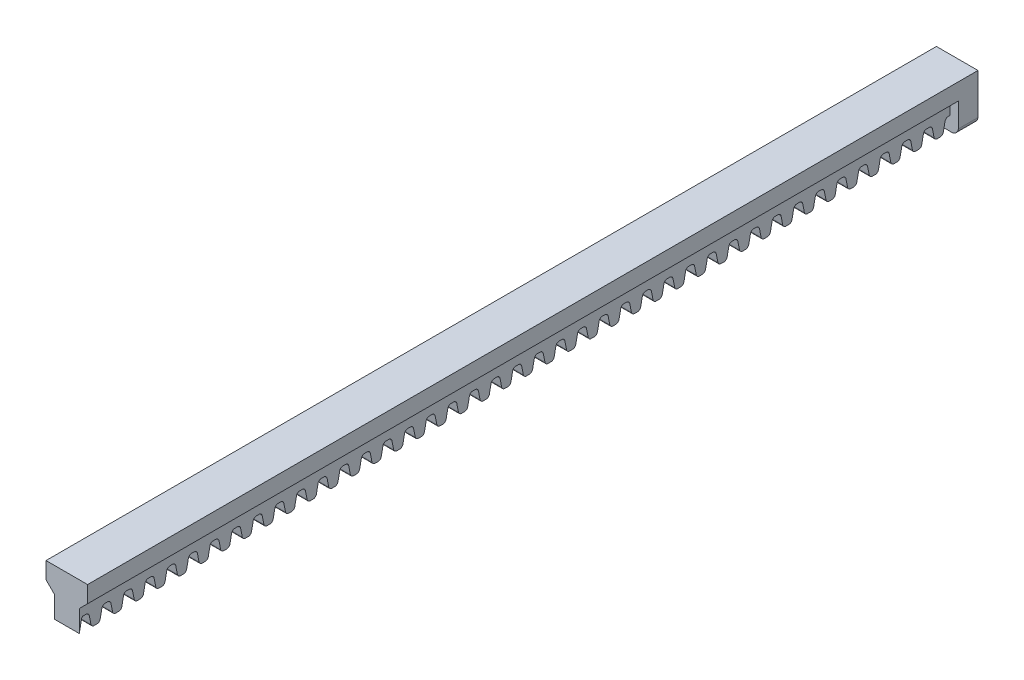
SolidWorks part; units mm, degrees
ref_plane "Ön Düzlem" through (0, 0, 0) normal (0, 0, 1) x (1, 0, 0)
ref_plane "Üst Düzlem" through (0, 0, 0) normal (0, 1, 0) x (1, 0, 0)
ref_plane "Sağ Düzlem" through (0, 0, 0) normal (1, 0, 0) x (0, 0, -1)
sketch "Sketch1" plane through (0, 0, 0) normal (0, 0, 1) x (1, 0, 0)
  line L0 (3.175, 2.54) -> (-3.175, 2.54)
  line L1 (3.175, 2.54) -> (3.175, 0)
  line L2 (-3.175, 0) -> (-1.905, -1.27)
  line L3 (-3.175, 0) -> (-3.175, 2.54)
  line L4 (1.905, -1.27) -> (3.175, 0)
  line L5 (1.905, -1.27) -> (1.905, -2.54)
  line L6 (-1.905, -1.27) -> (-1.905, -2.54)
  line L7 (-1.905, -2.54) -> (1.905, -2.54)
extrude "Boss-Extrude1" add sketch "Sketch1" along normal blind 133
sketch "Sketch2" plane through (1.905, 0, 0) normal (1, 0, 0) x (0, 0, -1)
  line L0 (-4.0649, -2.9484) -> (-4.3253, -4.2507)
  line L1 (-4.7367, -4.6515) -> (-5.2405, -4.659)
  line L2 (-5.7387, -4.2506) -> (-5.9991, -2.9484)
  line L3 (-6.4973, -2.54) -> (-3.5667, -2.54)
  line L4 (-109.7289, -2.9484) -> (-109.9893, -4.2506)
  line L5 (-6.8687, -2.54) -> (-9.7993, -2.54)
  line L6 (-7.6273, -4.2506) -> (-7.3669, -2.9484)
  line L7 (-8.6293, -4.6515) -> (-8.1255, -4.659)
  line L8 (-9.3011, -2.9484) -> (-9.0407, -4.2506)
  line L9 (-10.6689, -2.9484) -> (-10.9293, -4.2506)
  line L10 (-11.3407, -4.6515) -> (-11.8445, -4.659)
  line L11 (-12.3427, -4.2506) -> (-12.6031, -2.9484)
  line L12 (-13.1013, -2.54) -> (-10.1707, -2.54)
  line L13 (-13.4727, -2.54) -> (-16.4033, -2.54)
  line L14 (-14.2313, -4.2506) -> (-13.9709, -2.9484)
  line L15 (-15.2333, -4.6515) -> (-14.7295, -4.659)
  line L16 (-15.9051, -2.9484) -> (-15.6447, -4.2506)
  line L17 (-17.2729, -2.9484) -> (-17.5334, -4.2506)
  line L18 (-17.9447, -4.6515) -> (-18.4486, -4.659)
  line L19 (-18.9467, -4.2506) -> (-19.2072, -2.9484)
  line L20 (-19.7053, -2.54) -> (-16.7748, -2.54)
  line L21 (-20.0768, -2.54) -> (-23.0073, -2.54)
  line L22 (-20.8353, -4.2506) -> (-20.5749, -2.9484)
  line L23 (-21.8373, -4.6515) -> (-21.3335, -4.659)
  line L24 (-22.5092, -2.9484) -> (-22.2487, -4.2506)
  line L25 (-23.8769, -2.9484) -> (-24.1373, -4.2506)
  line L26 (-24.5487, -4.6515) -> (-25.0526, -4.659)
  line L27 (-25.5507, -4.2506) -> (-25.8111, -2.9484)
  line L28 (-26.3093, -2.54) -> (-23.3788, -2.54)
  line L29 (-26.6807, -2.54) -> (-29.6113, -2.54)
  line L30 (-27.4393, -4.2506) -> (-27.1789, -2.9484)
  line L31 (-28.4413, -4.6515) -> (-27.9375, -4.659)
  line L32 (-29.1131, -2.9484) -> (-28.8527, -4.2506)
  line L33 (-30.4809, -2.9484) -> (-30.7413, -4.2506)
  line L34 (-31.1527, -4.6515) -> (-31.6565, -4.659)
  line L35 (-32.1547, -4.2506) -> (-32.4151, -2.9484)
  line L36 (-32.9133, -2.54) -> (-29.9827, -2.54)
  line L37 (-33.2847, -2.54) -> (-36.2153, -2.54)
  line L38 (-34.0433, -4.2506) -> (-33.7829, -2.9484)
  line L39 (-35.0453, -4.6515) -> (-34.5415, -4.659)
  line L40 (-35.7171, -2.9484) -> (-35.4567, -4.2506)
  line L41 (-37.0849, -2.9484) -> (-37.3453, -4.2506)
  line L42 (-37.7567, -4.6515) -> (-38.2605, -4.659)
  line L43 (-38.7587, -4.2506) -> (-39.0191, -2.9484)
  line L44 (-39.5173, -2.54) -> (-36.5867, -2.54)
  line L45 (-39.8887, -2.54) -> (-42.8193, -2.54)
  line L46 (-40.6473, -4.2506) -> (-40.3869, -2.9484)
  line L47 (-41.6493, -4.6515) -> (-41.1455, -4.659)
  line L48 (-42.3211, -2.9484) -> (-42.0607, -4.2506)
  line L49 (-43.6889, -2.9484) -> (-43.9494, -4.2506)
  line L50 (-44.3607, -4.6515) -> (-44.8646, -4.659)
  line L51 (-45.3627, -4.2506) -> (-45.6231, -2.9484)
  line L52 (-46.1213, -2.54) -> (-43.1908, -2.54)
  line L53 (-46.4928, -2.54) -> (-49.4233, -2.54)
  line L54 (-47.2513, -4.2506) -> (-46.9909, -2.9484)
  line L55 (-48.2533, -4.6515) -> (-47.7495, -4.659)
  line L56 (-48.9251, -2.9484) -> (-48.6647, -4.2506)
  line L57 (-50.2929, -2.9484) -> (-50.5533, -4.2506)
  line L58 (-50.9647, -4.6515) -> (-51.4685, -4.659)
  line L59 (-51.9667, -4.2506) -> (-52.2271, -2.9484)
  line L60 (-52.7253, -2.54) -> (-49.7947, -2.54)
  line L61 (-53.0967, -2.54) -> (-56.0273, -2.54)
  line L62 (-53.8553, -4.2506) -> (-53.5949, -2.9484)
  line L63 (-54.8573, -4.6515) -> (-54.3535, -4.659)
  line L64 (-55.5291, -2.9484) -> (-55.2687, -4.2506)
  line L65 (-56.8969, -2.9484) -> (-57.1573, -4.2506)
  line L66 (-57.5687, -4.6515) -> (-58.0725, -4.659)
  line L67 (-58.5707, -4.2506) -> (-58.8311, -2.9484)
  line L68 (-59.3293, -2.54) -> (-56.3987, -2.54)
  line L69 (-59.7007, -2.54) -> (-62.6313, -2.54)
  line L70 (-60.4593, -4.2506) -> (-60.1989, -2.9484)
  line L71 (-61.4613, -4.6515) -> (-60.9575, -4.659)
  line L72 (-62.1331, -2.9484) -> (-61.8727, -4.2506)
  line L73 (-63.5009, -2.9484) -> (-63.7613, -4.2506)
  line L74 (-64.1727, -4.6515) -> (-64.6765, -4.659)
  line L75 (-65.1747, -4.2506) -> (-65.4351, -2.9484)
  line L76 (-65.9332, -2.54) -> (-63.0027, -2.54)
  line L77 (-66.3047, -2.54) -> (-69.2353, -2.54)
  line L78 (-67.0633, -4.2506) -> (-66.8029, -2.9484)
  line L79 (-68.0653, -4.6515) -> (-67.5614, -4.659)
  line L80 (-68.7371, -2.9484) -> (-68.4767, -4.2506)
  line L81 (-70.1049, -2.9484) -> (-70.3653, -4.2506)
  line L82 (-70.7767, -4.6515) -> (-71.2806, -4.659)
  line L83 (-71.7787, -4.2506) -> (-72.0391, -2.9484)
  line L84 (-72.5373, -2.54) -> (-69.6068, -2.54)
  line L85 (-72.9088, -2.54) -> (-75.8393, -2.54)
  line L86 (-73.6673, -4.2506) -> (-73.4069, -2.9484)
  line L87 (-74.6693, -4.6515) -> (-74.1655, -4.659)
  line L88 (-75.3411, -2.9484) -> (-75.0807, -4.2506)
  line L89 (-76.7089, -2.9484) -> (-76.9693, -4.2506)
  line L90 (-77.3807, -4.6515) -> (-77.8845, -4.659)
  line L91 (-78.3827, -4.2506) -> (-78.6431, -2.9484)
  line L92 (-79.1413, -2.54) -> (-76.2107, -2.54)
  line L93 (-79.5127, -2.54) -> (-82.4433, -2.54)
  line L94 (-80.2713, -4.2506) -> (-80.0109, -2.9484)
  line L95 (-81.2733, -4.6515) -> (-80.7695, -4.659)
  line L96 (-81.9451, -2.9484) -> (-81.6847, -4.2506)
  line L97 (-83.3129, -2.9484) -> (-83.5733, -4.2506)
  line L98 (-83.9847, -4.6515) -> (-84.4885, -4.659)
  line L99 (-84.9867, -4.2506) -> (-85.2471, -2.9484)
  line L100 (-85.7453, -2.54) -> (-82.8147, -2.54)
  line L101 (-86.1167, -2.54) -> (-89.0473, -2.54)
  line L102 (-86.8753, -4.2506) -> (-86.6149, -2.9484)
  line L103 (-87.8773, -4.6515) -> (-87.3735, -4.659)
  line L104 (-88.5491, -2.9484) -> (-88.2887, -4.2506)
  line L105 (-89.9169, -2.9484) -> (-90.1773, -4.2506)
  line L106 (-90.5887, -4.6515) -> (-91.0925, -4.659)
  line L107 (-91.5907, -4.2506) -> (-91.8511, -2.9484)
  line L108 (-92.3492, -2.54) -> (-89.4187, -2.54)
  line L109 (-92.7207, -2.54) -> (-95.6513, -2.54)
  line L110 (-93.4793, -4.2506) -> (-93.2189, -2.9484)
  line L111 (-94.4813, -4.6515) -> (-93.9774, -4.659)
  line L112 (-95.1531, -2.9484) -> (-94.8927, -4.2506)
  line L113 (-96.5209, -2.9484) -> (-96.7813, -4.2506)
  line L114 (-97.1927, -4.6515) -> (-97.6966, -4.659)
  line L115 (-98.1947, -4.2506) -> (-98.4551, -2.9484)
  line L116 (-98.9533, -2.54) -> (-96.0228, -2.54)
  line L117 (-99.3247, -2.54) -> (-102.2553, -2.54)
  line L118 (-100.0833, -4.2506) -> (-99.8229, -2.9484)
  line L119 (-101.0853, -4.6515) -> (-100.5815, -4.659)
  line L120 (-101.7571, -2.9484) -> (-101.4967, -4.2506)
  line L121 (-103.1249, -2.9484) -> (-103.3853, -4.2506)
  line L122 (-103.7967, -4.6515) -> (-104.3005, -4.659)
  line L123 (-104.7987, -4.2506) -> (-105.0591, -2.9484)
  line L124 (-105.5573, -2.54) -> (-102.6267, -2.54)
  line L125 (-105.9287, -2.54) -> (-108.8593, -2.54)
  line L126 (-106.6873, -4.2506) -> (-106.4269, -2.9484)
  line L127 (-107.6893, -4.6515) -> (-107.1855, -4.659)
  line L128 (-108.3611, -2.9484) -> (-108.1007, -4.2506)
  line L129 (-110.4007, -4.6515) -> (-110.9045, -4.659)
  line L130 (-111.4027, -4.2506) -> (-111.6631, -2.9484)
  line L131 (-112.1613, -2.54) -> (-109.2307, -2.54)
  line L132 (-112.5327, -2.54) -> (-115.4633, -2.54)
  line L133 (-113.2913, -4.2506) -> (-113.0309, -2.9484)
  line L134 (-114.2933, -4.6515) -> (-113.7895, -4.659)
  line L135 (-114.9651, -2.9484) -> (-114.7047, -4.2506)
  line L136 (-116.3329, -2.9484) -> (-116.5933, -4.2506)
  line L137 (-117.0047, -4.6515) -> (-117.5085, -4.659)
  line L138 (-118.0067, -4.2506) -> (-118.2671, -2.9484)
  line L139 (-118.7652, -2.54) -> (-115.8347, -2.54)
  line L140 (-119.1367, -2.54) -> (-122.0673, -2.54)
  line L141 (-119.8953, -4.2506) -> (-119.6349, -2.9484)
  line L142 (-120.8973, -4.6515) -> (-120.3934, -4.659)
  line L143 (-121.5691, -2.9484) -> (-121.3087, -4.2506)
  line L144 (-122.9369, -2.9484) -> (-123.1973, -4.2506)
  line L145 (-123.6087, -4.6515) -> (-124.1126, -4.659)
  line L146 (-124.6107, -4.2506) -> (-124.8711, -2.9484)
  line L147 (-125.3693, -2.54) -> (-122.4388, -2.54)
  line L148 (-125.7408, -2.54) -> (-128.6713, -2.54)
  line L149 (-126.4993, -4.2506) -> (-126.2389, -2.9484)
  line L150 (-127.5013, -4.6515) -> (-126.9975, -4.659)
  line L151 (-128.1731, -2.9484) -> (-127.9127, -4.2506)
  line L152 (-129.5409, -2.9484) -> (-129.8013, -4.2506)
  line L153 (-130.2127, -4.6515) -> (-130.7165, -4.659)
  line L154 (-131.2147, -4.2506) -> (-131.4751, -2.9484)
  line L155 (-131.9733, -2.54) -> (-129.0427, -2.54)
  line L156 (-133, -2.54) -> (-133, -4.5784)
  line L157 (-133, -4.5784) -> (-132.6341, -2.749)
  line L158 (-133, -2.54) -> (-132.3792, -2.54)
  line L160 (-133, -2.54) -> (0, -2.54) construction
  line L161 (-133, -2.54) -> (-133, -1.27) construction
  line L163 (-0.2651, -2.54) -> (-3.1956, -2.54)
  line L164 (-1.0237, -4.2506) -> (-0.7632, -2.9484)
  line L165 (-2.0257, -4.6515) -> (-1.5218, -4.659)
  line L166 (-2.6975, -2.9484) -> (-2.437, -4.2507)
  arc A0 (-4.0649, -2.9484) -> (-3.5667, -2.54) centre (-3.5667, -3.048) cw
  arc A1 (-4.3253, -4.2507) -> (-4.7367, -4.6515) centre (-4.8234, -4.151) cw
  arc A2 (-5.2405, -4.659) -> (-5.7387, -4.2506) centre (-5.2405, -4.151) cw
  arc A3 (-5.9991, -2.9484) -> (-6.4973, -2.54) centre (-6.4973, -3.048) ccw
  arc A4 (-7.3669, -2.9484) -> (-6.8687, -2.54) centre (-6.8687, -3.048) cw
  arc A5 (-8.1255, -4.659) -> (-7.6273, -4.2506) centre (-8.1255, -4.151) ccw
  arc A6 (-9.0407, -4.2506) -> (-8.6293, -4.6515) centre (-8.5425, -4.151) ccw
  arc A7 (-9.3011, -2.9484) -> (-9.7993, -2.54) centre (-9.7993, -3.048) ccw
  arc A8 (-10.6689, -2.9484) -> (-10.1707, -2.54) centre (-10.1707, -3.048) cw
  arc A9 (-10.9293, -4.2506) -> (-11.3407, -4.6515) centre (-11.4275, -4.151) cw
  arc A10 (-11.8445, -4.659) -> (-12.3427, -4.2506) centre (-11.8445, -4.151) cw
  arc A11 (-12.6031, -2.9484) -> (-13.1013, -2.54) centre (-13.1013, -3.048) ccw
  arc A12 (-13.9709, -2.9484) -> (-13.4727, -2.54) centre (-13.4727, -3.048) cw
  arc A13 (-14.7295, -4.659) -> (-14.2313, -4.2506) centre (-14.7294, -4.151) ccw
  arc A14 (-15.6447, -4.2506) -> (-15.2333, -4.6515) centre (-15.1465, -4.151) ccw
  arc A15 (-15.9051, -2.9484) -> (-16.4033, -2.54) centre (-16.4033, -3.048) ccw
  arc A16 (-17.2729, -2.9484) -> (-16.7748, -2.54) centre (-16.7748, -3.048) cw
  arc A17 (-17.5334, -4.2506) -> (-17.9447, -4.6515) centre (-18.0315, -4.151) cw
  arc A18 (-18.4486, -4.659) -> (-18.9467, -4.2506) centre (-18.4486, -4.151) cw
  arc A19 (-19.2072, -2.9484) -> (-19.7053, -2.54) centre (-19.7053, -3.048) ccw
  arc A20 (-20.5749, -2.9484) -> (-20.0768, -2.54) centre (-20.0768, -3.048) cw
  arc A21 (-21.3335, -4.659) -> (-20.8353, -4.2506) centre (-21.3335, -4.151) ccw
  arc A22 (-22.2487, -4.2506) -> (-21.8373, -4.6515) centre (-21.7506, -4.151) ccw
  arc A23 (-22.5092, -2.9484) -> (-23.0073, -2.54) centre (-23.0073, -3.048) ccw
  arc A24 (-23.8769, -2.9484) -> (-23.3788, -2.54) centre (-23.3787, -3.048) cw
  arc A25 (-24.1373, -4.2506) -> (-24.5487, -4.6515) centre (-24.6355, -4.151) cw
  arc A26 (-25.0526, -4.659) -> (-25.5507, -4.2506) centre (-25.0526, -4.151) cw
  arc A27 (-25.8111, -2.9484) -> (-26.3093, -2.54) centre (-26.3093, -3.048) ccw
  arc A28 (-27.1789, -2.9484) -> (-26.6807, -2.54) centre (-26.6808, -3.048) cw
  arc A29 (-27.9375, -4.659) -> (-27.4393, -4.2506) centre (-27.9375, -4.151) ccw
  arc A30 (-28.8527, -4.2506) -> (-28.4413, -4.6515) centre (-28.3546, -4.151) ccw
  arc A31 (-29.1131, -2.9484) -> (-29.6113, -2.54) centre (-29.6113, -3.048) ccw
  arc A32 (-30.4809, -2.9484) -> (-29.9827, -2.54) centre (-29.9827, -3.048) cw
  arc A33 (-30.7413, -4.2506) -> (-31.1527, -4.6515) centre (-31.2394, -4.151) cw
  arc A34 (-31.6565, -4.659) -> (-32.1547, -4.2506) centre (-31.6565, -4.151) cw
  arc A35 (-32.4151, -2.9484) -> (-32.9133, -2.54) centre (-32.9133, -3.048) ccw
  arc A36 (-33.7829, -2.9484) -> (-33.2847, -2.54) centre (-33.2847, -3.048) cw
  arc A37 (-34.5415, -4.659) -> (-34.0433, -4.2506) centre (-34.5415, -4.151) ccw
  arc A38 (-35.4567, -4.2506) -> (-35.0453, -4.6515) centre (-34.9585, -4.151) ccw
  arc A39 (-35.7171, -2.9484) -> (-36.2153, -2.54) centre (-36.2153, -3.048) ccw
  arc A40 (-37.0849, -2.9484) -> (-36.5867, -2.54) centre (-36.5867, -3.048) cw
  arc A41 (-37.3453, -4.2506) -> (-37.7567, -4.6515) centre (-37.8435, -4.151) cw
  arc A42 (-38.2605, -4.659) -> (-38.7587, -4.2506) centre (-38.2605, -4.151) cw
  arc A43 (-39.0191, -2.9484) -> (-39.5173, -2.54) centre (-39.5173, -3.048) ccw
  arc A44 (-40.3869, -2.9484) -> (-39.8887, -2.54) centre (-39.8887, -3.048) cw
  arc A45 (-41.1455, -4.659) -> (-40.6473, -4.2506) centre (-41.1454, -4.151) ccw
  arc A46 (-42.0607, -4.2506) -> (-41.6493, -4.6515) centre (-41.5625, -4.151) ccw
  arc A47 (-42.3211, -2.9484) -> (-42.8193, -2.54) centre (-42.8193, -3.048) ccw
  arc A48 (-43.6889, -2.9484) -> (-43.1908, -2.54) centre (-43.1908, -3.048) cw
  arc A49 (-43.9494, -4.2506) -> (-44.3607, -4.6515) centre (-44.4475, -4.151) cw
  arc A50 (-44.8646, -4.659) -> (-45.3627, -4.2506) centre (-44.8646, -4.151) cw
  arc A51 (-45.6231, -2.9484) -> (-46.1213, -2.54) centre (-46.1213, -3.048) ccw
  arc A52 (-46.9909, -2.9484) -> (-46.4928, -2.54) centre (-46.4928, -3.048) cw
  arc A53 (-47.7495, -4.659) -> (-47.2513, -4.2506) centre (-47.7495, -4.151) ccw
  arc A54 (-48.6647, -4.2506) -> (-48.2533, -4.6515) centre (-48.1666, -4.151) ccw
  arc A55 (-48.9251, -2.9484) -> (-49.4233, -2.54) centre (-49.4233, -3.048) ccw
  arc A56 (-50.2929, -2.9484) -> (-49.7947, -2.54) centre (-49.7947, -3.048) cw
  arc A57 (-50.5533, -4.2506) -> (-50.9647, -4.6515) centre (-51.0515, -4.151) cw
  arc A58 (-51.4685, -4.659) -> (-51.9667, -4.2506) centre (-51.4686, -4.151) cw
  arc A59 (-52.2271, -2.9484) -> (-52.7253, -2.54) centre (-52.7253, -3.048) ccw
  arc A60 (-53.5949, -2.9484) -> (-53.0967, -2.54) centre (-53.0967, -3.048) cw
  arc A61 (-54.3535, -4.659) -> (-53.8553, -4.2506) centre (-54.3535, -4.151) ccw
  arc A62 (-55.2687, -4.2506) -> (-54.8573, -4.6515) centre (-54.7706, -4.151) ccw
  arc A63 (-55.5291, -2.9484) -> (-56.0273, -2.54) centre (-56.0273, -3.048) ccw
  arc A64 (-56.8969, -2.9484) -> (-56.3987, -2.54) centre (-56.3987, -3.048) cw
  arc A65 (-57.1573, -4.2506) -> (-57.5687, -4.6515) centre (-57.6554, -4.151) cw
  arc A66 (-58.0725, -4.659) -> (-58.5707, -4.2506) centre (-58.0725, -4.151) cw
  arc A67 (-58.8311, -2.9484) -> (-59.3293, -2.54) centre (-59.3293, -3.048) ccw
  arc A68 (-60.1989, -2.9484) -> (-59.7007, -2.54) centre (-59.7007, -3.048) cw
  arc A69 (-60.9575, -4.659) -> (-60.4593, -4.2506) centre (-60.9575, -4.151) ccw
  arc A70 (-61.8727, -4.2506) -> (-61.4613, -4.6515) centre (-61.3745, -4.151) ccw
  arc A71 (-62.1331, -2.9484) -> (-62.6313, -2.54) centre (-62.6313, -3.048) ccw
  arc A72 (-63.5009, -2.9484) -> (-63.0027, -2.54) centre (-63.0027, -3.048) cw
  arc A73 (-63.7613, -4.2506) -> (-64.1727, -4.6515) centre (-64.2594, -4.151) cw
  arc A74 (-64.6765, -4.659) -> (-65.1747, -4.2506) centre (-64.6765, -4.151) cw
  arc A75 (-65.4351, -2.9484) -> (-65.9332, -2.54) centre (-65.9332, -3.048) ccw
  arc A76 (-66.8029, -2.9484) -> (-66.3047, -2.54) centre (-66.3047, -3.048) cw
  arc A77 (-67.5614, -4.659) -> (-67.0633, -4.2506) centre (-67.5614, -4.151) ccw
  arc A78 (-68.4767, -4.2506) -> (-68.0653, -4.6515) centre (-67.9785, -4.151) ccw
  arc A79 (-68.7371, -2.9484) -> (-69.2353, -2.54) centre (-69.2353, -3.048) ccw
  arc A80 (-70.1049, -2.9484) -> (-69.6068, -2.54) centre (-69.6067, -3.048) cw
  arc A81 (-70.3653, -4.2506) -> (-70.7767, -4.6515) centre (-70.8635, -4.151) cw
  arc A82 (-71.2806, -4.659) -> (-71.7787, -4.2506) centre (-71.2806, -4.151) cw
  arc A83 (-72.0391, -2.9484) -> (-72.5373, -2.54) centre (-72.5373, -3.048) ccw
  arc A84 (-73.4069, -2.9484) -> (-72.9088, -2.54) centre (-72.9088, -3.048) cw
  arc A85 (-74.1655, -4.659) -> (-73.6673, -4.2506) centre (-74.1655, -4.151) ccw
  arc A86 (-75.0807, -4.2506) -> (-74.6693, -4.6515) centre (-74.5826, -4.151) ccw
  arc A87 (-75.3411, -2.9484) -> (-75.8393, -2.54) centre (-75.8393, -3.048) ccw
  arc A88 (-76.7089, -2.9484) -> (-76.2107, -2.54) centre (-76.2107, -3.048) cw
  arc A89 (-76.9693, -4.2506) -> (-77.3807, -4.6515) centre (-77.4675, -4.151) cw
  arc A90 (-77.8845, -4.659) -> (-78.3827, -4.2506) centre (-77.8845, -4.151) cw
  arc A91 (-78.6431, -2.9484) -> (-79.1413, -2.54) centre (-79.1413, -3.048) ccw
  arc A92 (-80.0109, -2.9484) -> (-79.5127, -2.54) centre (-79.5127, -3.048) cw
  arc A93 (-80.7695, -4.659) -> (-80.2713, -4.2506) centre (-80.7695, -4.151) ccw
  arc A94 (-81.6847, -4.2506) -> (-81.2733, -4.6515) centre (-81.1866, -4.151) ccw
  arc A95 (-81.9451, -2.9484) -> (-82.4433, -2.54) centre (-82.4433, -3.048) ccw
  arc A96 (-83.3129, -2.9484) -> (-82.8147, -2.54) centre (-82.8147, -3.048) cw
  arc A97 (-83.5733, -4.2506) -> (-83.9847, -4.6515) centre (-84.0714, -4.151) cw
  arc A98 (-84.4885, -4.659) -> (-84.9867, -4.2506) centre (-84.4885, -4.151) cw
  arc A99 (-85.2471, -2.9484) -> (-85.7453, -2.54) centre (-85.7453, -3.048) ccw
  arc A100 (-86.6149, -2.9484) -> (-86.1167, -2.54) centre (-86.1167, -3.048) cw
  arc A101 (-87.3735, -4.659) -> (-86.8753, -4.2506) centre (-87.3735, -4.151) ccw
  arc A102 (-88.2887, -4.2506) -> (-87.8773, -4.6515) centre (-87.7905, -4.151) ccw
  arc A103 (-88.5491, -2.9484) -> (-89.0473, -2.54) centre (-89.0473, -3.048) ccw
  arc A104 (-89.9169, -2.9484) -> (-89.4187, -2.54) centre (-89.4187, -3.048) cw
  arc A105 (-90.1773, -4.2506) -> (-90.5887, -4.6515) centre (-90.6754, -4.151) cw
  arc A106 (-91.0925, -4.659) -> (-91.5907, -4.2506) centre (-91.0925, -4.151) cw
  arc A107 (-91.8511, -2.9484) -> (-92.3492, -2.54) centre (-92.3492, -3.048) ccw
  arc A108 (-93.2189, -2.9484) -> (-92.7207, -2.54) centre (-92.7207, -3.048) cw
  arc A109 (-93.9774, -4.659) -> (-93.4793, -4.2506) centre (-93.9774, -4.151) ccw
  arc A110 (-94.8927, -4.2506) -> (-94.4813, -4.6515) centre (-94.3945, -4.151) ccw
  arc A111 (-95.1531, -2.9484) -> (-95.6513, -2.54) centre (-95.6513, -3.048) ccw
  arc A112 (-96.5209, -2.9484) -> (-96.0228, -2.54) centre (-96.0227, -3.048) cw
  arc A113 (-96.7813, -4.2506) -> (-97.1927, -4.6515) centre (-97.2795, -4.151) cw
  arc A114 (-97.6966, -4.659) -> (-98.1947, -4.2506) centre (-97.6966, -4.151) cw
  arc A115 (-98.4551, -2.9484) -> (-98.9533, -2.54) centre (-98.9533, -3.048) ccw
  arc A116 (-99.8229, -2.9484) -> (-99.3247, -2.54) centre (-99.3248, -3.048) cw
  arc A117 (-100.5815, -4.659) -> (-100.0833, -4.2506) centre (-100.5815, -4.151) ccw
  arc A118 (-101.4967, -4.2506) -> (-101.0853, -4.6515) centre (-100.9986, -4.151) ccw
  arc A119 (-101.7571, -2.9484) -> (-102.2553, -2.54) centre (-102.2553, -3.048) ccw
  arc A120 (-103.1249, -2.9484) -> (-102.6267, -2.54) centre (-102.6267, -3.048) cw
  arc A121 (-103.3853, -4.2506) -> (-103.7967, -4.6515) centre (-103.8835, -4.151) cw
  arc A122 (-104.3005, -4.659) -> (-104.7987, -4.2506) centre (-104.3005, -4.151) cw
  arc A123 (-105.0591, -2.9484) -> (-105.5573, -2.54) centre (-105.5573, -3.048) ccw
  arc A124 (-106.4269, -2.9484) -> (-105.9287, -2.54) centre (-105.9287, -3.048) cw
  arc A125 (-107.1855, -4.659) -> (-106.6873, -4.2506) centre (-107.1855, -4.151) ccw
  arc A126 (-108.1007, -4.2506) -> (-107.6893, -4.6515) centre (-107.6026, -4.151) ccw
  arc A127 (-108.3611, -2.9484) -> (-108.8593, -2.54) centre (-108.8593, -3.048) ccw
  arc A128 (-109.7289, -2.9484) -> (-109.2307, -2.54) centre (-109.2307, -3.048) cw
  arc A129 (-109.9893, -4.2506) -> (-110.4007, -4.6515) centre (-110.4874, -4.151) cw
  arc A130 (-110.9045, -4.659) -> (-111.4027, -4.2506) centre (-110.9045, -4.151) cw
  arc A131 (-111.6631, -2.9484) -> (-112.1613, -2.54) centre (-112.1613, -3.048) ccw
  arc A132 (-113.0309, -2.9484) -> (-112.5327, -2.54) centre (-112.5327, -3.048) cw
  arc A133 (-113.7895, -4.659) -> (-113.2913, -4.2506) centre (-113.7895, -4.151) ccw
  arc A134 (-114.7047, -4.2506) -> (-114.2933, -4.6515) centre (-114.2065, -4.151) ccw
  arc A135 (-114.9651, -2.9484) -> (-115.4633, -2.54) centre (-115.4633, -3.048) ccw
  arc A136 (-116.3329, -2.9484) -> (-115.8347, -2.54) centre (-115.8347, -3.048) cw
  arc A137 (-116.5933, -4.2506) -> (-117.0047, -4.6515) centre (-117.0914, -4.151) cw
  arc A138 (-117.5085, -4.659) -> (-118.0067, -4.2506) centre (-117.5085, -4.151) cw
  arc A139 (-118.2671, -2.9484) -> (-118.7652, -2.54) centre (-118.7652, -3.048) ccw
  arc A140 (-119.6349, -2.9484) -> (-119.1367, -2.54) centre (-119.1367, -3.048) cw
  arc A141 (-120.3934, -4.659) -> (-119.8953, -4.2506) centre (-120.3934, -4.151) ccw
  arc A142 (-121.3087, -4.2506) -> (-120.8973, -4.6515) centre (-120.8105, -4.151) ccw
  arc A143 (-121.5691, -2.9484) -> (-122.0673, -2.54) centre (-122.0673, -3.048) ccw
  arc A144 (-122.9369, -2.9484) -> (-122.4388, -2.54) centre (-122.4387, -3.048) cw
  arc A145 (-123.1973, -4.2506) -> (-123.6087, -4.6515) centre (-123.6955, -4.151) cw
  arc A146 (-124.1126, -4.659) -> (-124.6107, -4.2506) centre (-124.1126, -4.151) cw
  arc A147 (-124.8711, -2.9484) -> (-125.3693, -2.54) centre (-125.3693, -3.048) ccw
  arc A148 (-126.2389, -2.9484) -> (-125.7408, -2.54) centre (-125.7408, -3.048) cw
  arc A149 (-126.9975, -4.659) -> (-126.4993, -4.2506) centre (-126.9975, -4.151) ccw
  arc A150 (-127.9127, -4.2506) -> (-127.5013, -4.6515) centre (-127.4146, -4.151) ccw
  arc A151 (-128.1731, -2.9484) -> (-128.6713, -2.54) centre (-128.6713, -3.048) ccw
  arc A152 (-129.5409, -2.9484) -> (-129.0427, -2.54) centre (-129.0427, -3.048) cw
  arc A153 (-129.8013, -4.2506) -> (-130.2127, -4.6515) centre (-130.2995, -4.151) cw
  arc A154 (-130.7165, -4.659) -> (-131.2147, -4.2506) centre (-130.7165, -4.151) cw
  arc A155 (-131.4751, -2.9484) -> (-131.9733, -2.54) centre (-131.9733, -3.048) ccw
  arc A156 (-132.6341, -2.749) -> (-132.3792, -2.54) centre (-132.3792, -2.7999) cw
  arc A157 (-0.7632, -2.9484) -> (-0.2651, -2.54) centre (-0.2651, -3.048) cw
  arc A158 (-1.5218, -4.659) -> (-1.0237, -4.2506) centre (-1.5218, -4.151) ccw
  arc A159 (-2.437, -4.2507) -> (-2.0257, -4.6515) centre (-1.9389, -4.151) ccw
  arc A160 (-2.6975, -2.9484) -> (-3.1956, -2.54) centre (-3.1956, -3.048) ccw
  point P473 (0, 0)
extrude "Boss-Extrude2" add sketch "Sketch2" against normal up to surface (3.81 mm away) up to face at (-1.905, -1.905, 66.5)
sketch "Sketch3" plane through (0, 0, 0) normal (0, 0, -1) x (-1, 0, 0)
  line L0 (-3.175, 2.54) -> (-3.175, -3.6837)
  line L1 (3.175, 2.54) -> (3.175, -3.6837)
  line L2 (-3.175, 2.54) -> (3.175, 2.54)
  line L7 (1.905, -4.659) -> (1.905, -4.6515)
  line L8 (-1.905, -4.659) -> (1.905, -4.659)
  line L9 (-1.905, -4.6515) -> (-1.905, -4.659)
  line L10 (1.905, -4.6515) -> (-1.905, -4.6515)
  line L11 (1.905, -4.659) -> (1.905, -4.6515)
  line L13 (-1.905, -4.6515) -> (-1.905, -4.659)
  line L14 (1.905, -4.6515) -> (-1.905, -4.6515)
  arc A0 (-3.175, -3.6837) -> (-1.905, -4.659) centre (-2.0523, -3.5363) ccw
  arc A1 (3.175, -3.6837) -> (1.905, -4.659) centre (2.0523, -3.5363) cw
  dimension "D1" = 0
extrude "Boss-Extrude4" add sketch "Sketch3" along normal blind 3
